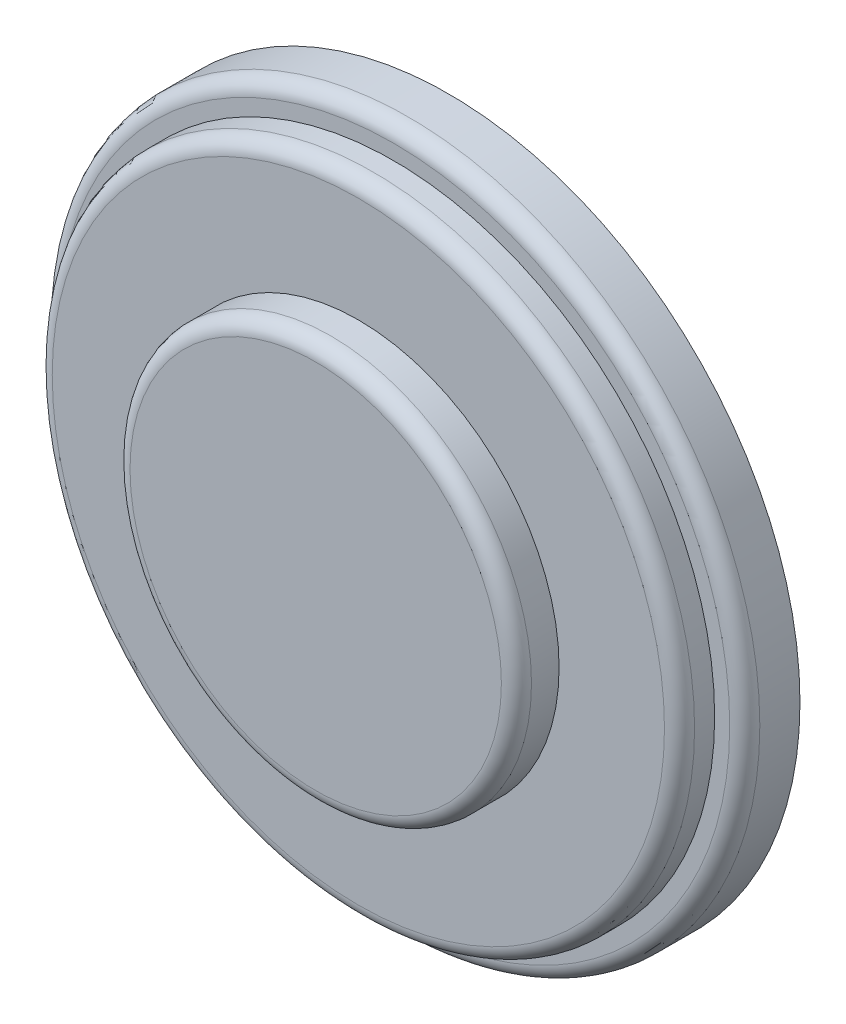
SolidWorks part; units mm, degrees
ref_plane "Plan de face" through (0, 0, 0) normal (0, 0, 1) x (1, 0, 0)
ref_plane "Plan de dessus" through (0, 0, 0) normal (0, 1, 0) x (1, 0, 0)
ref_plane "Plan de droite" through (0, 0, 0) normal (1, 0, 0) x (0, 0, -1)
sketch "Esquisse1" plane through (0, 0, 0) normal (0, 0, 1) x (1, 0, 0)
  circle A0 centre (0, 0) radius 14
  dimension "D1" = 28
extrude "Boss.-Extru.1" add sketch "Esquisse1" along normal blind 2.2
sketch "Esquisse2" plane through (0, 0, 2.2) normal (0, 0, 1) x (1, 0, 0)
  circle A0 centre (0, 0) radius 12.8
  dimension "D1" = 25.6
extrude "Boss.-Extru.2" add sketch "Esquisse2" along normal blind 1.4
sketch "Esquisse3" plane through (0, 0, 3.6) normal (0, 0, 1) x (1, 0, 0)
  circle A0 centre (0, 0) radius 8
  dimension "D1" = 16
extrude "Boss.-Extru.3" add sketch "Esquisse3" along normal blind 1.7
sketch "Esquisse4" plane through (0, 0, 0) normal (0, 0, -1) x (-1, 0, 0)
  circle A0 centre (0, 0) radius 12.5
  dimension "D1" = 25
extrude "Enlèv. mat.-Extru.1" cut sketch "Esquisse4" against normal blind 1
fillet "Congé1" radius 0.6 3 edges at (8, 0, 5.3) (12.8, 0, 3.6) (14, 0, 2.2)
equation "\"D1@Boss.-Extru.2\"=3.6-2.2"
